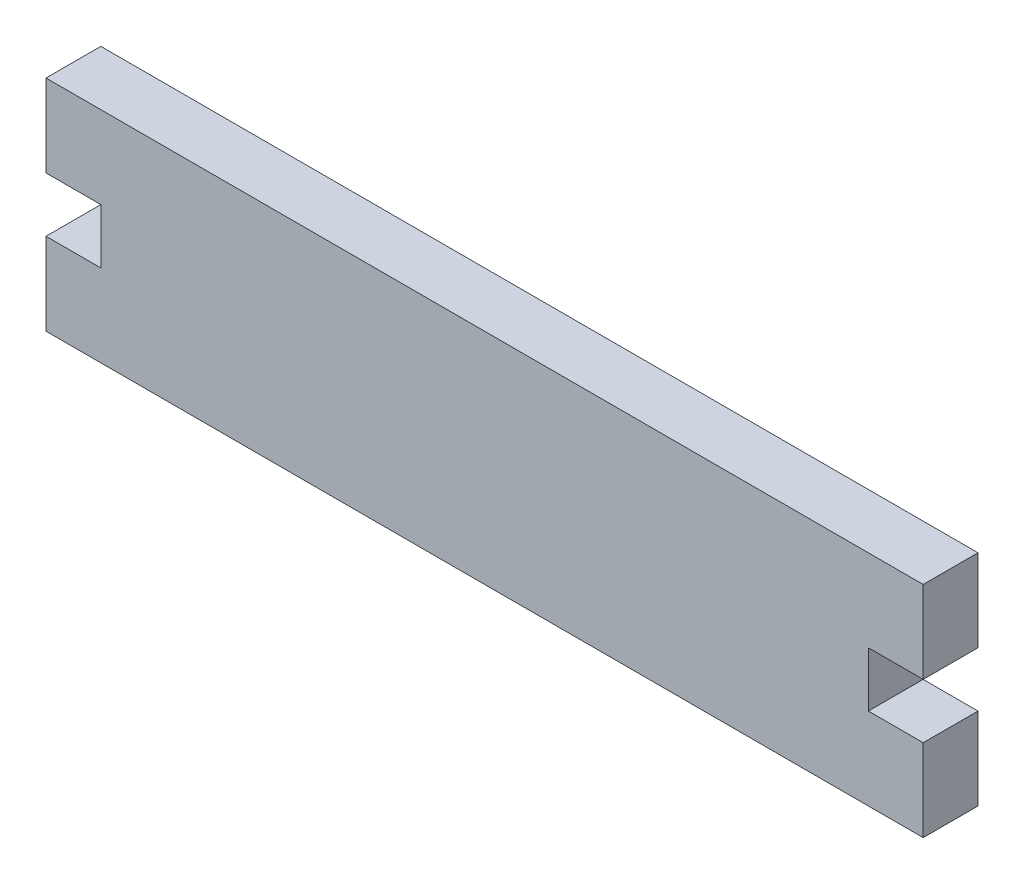
SolidWorks part; units mm, degrees
ref_plane "Plan de face" through (0, 0, 0) normal (0, 0, 1) x (1, 0, 0)
ref_plane "Plan de dessus" through (0, 0, 0) normal (0, 1, 0) x (1, 0, 0)
ref_plane "Plan de droite" through (0, 0, 0) normal (1, 0, 0) x (0, 0, -1)
sketch "Esquisse1" plane through (0, 0, 0) normal (0, 0, 1) x (1, 0, 0)
  line L0 (35, 0) -> (35, 20) construction
  line L1 (0, 0) -> (70, 0)
  line L2 (0, 7.5) -> (0, 12.5)
  line L3 (0, 20) -> (70, 20)
  line L4 (70, 7.5) -> (70, 12.5)
  line L5 (70, 0) -> (75, 0)
  line L6 (0, 20) -> (-5, 20)
  line L8 (0, 12.5) -> (-5, 12.5)
  line L9 (-5, 20) -> (-5, 12.5)
  line L10 (0, 0) -> (-5, 0)
  line L12 (0, 7.5) -> (-5, 7.5)
  line L13 (-5, 0) -> (-5, 7.5)
  line L14 (75, 0) -> (75, 7.5)
  line L15 (70, 7.5) -> (75, 7.5)
  line L16 (70, 12.5) -> (75, 12.5)
  line L17 (75, 20) -> (75, 12.5)
  line L18 (70, 20) -> (75, 20)
  dimension "D1" = 70
  dimension "D2" = 20
  dimension "D4" = 7.5
  dimension "D5" = 5
extrude "Boss.-Extru.1" add sketch "Esquisse1" along normal blind 5
